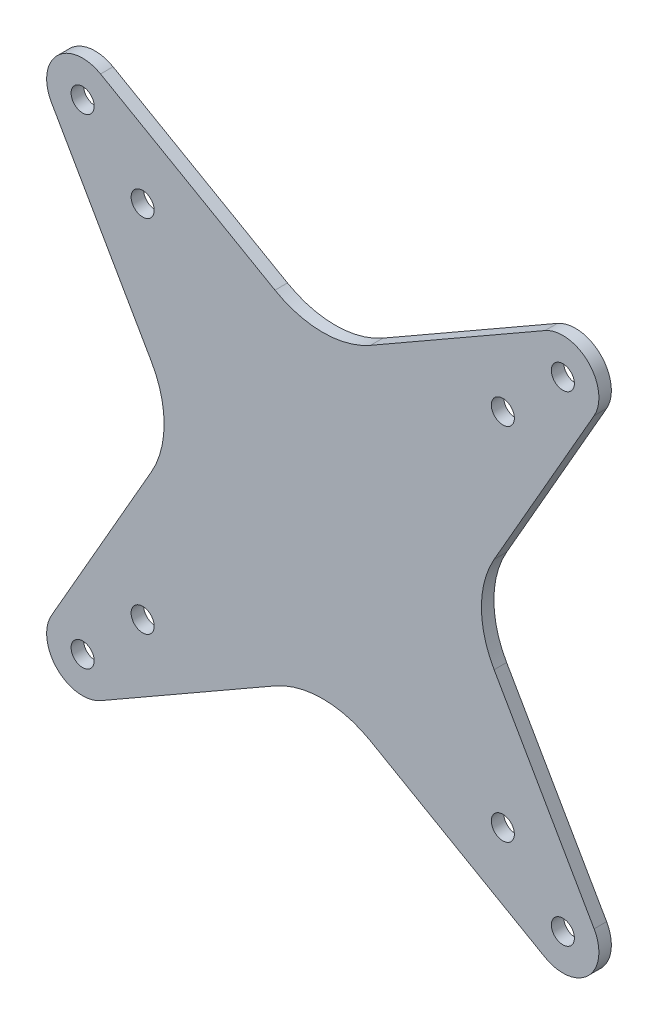
SolidWorks part; units mm, degrees
ref_plane "Front Plane" through (0, 0, 0) normal (0, 0, 1) x (1, 0, 0)
ref_plane "Top Plane" through (0, 0, 0) normal (0, 1, 0) x (1, 0, 0)
ref_plane "Right Plane" through (0, 0, 0) normal (1, 0, 0) x (0, 0, -1)
sketch "Sketch1" plane through (0, 0, 0) normal (0, 0, 1) x (1, 0, 0)
  line L0 (-53.033, 0) -> (0, -53.033) construction
  line L1 (-37.5, -37.5) -> (37.5, -37.5) construction
  line L2 (-37.5, -37.5) -> (-37.5, 37.5) construction
  line L3 (-37.5, 37.5) -> (37.5, 37.5) construction
  line L4 (37.5, -37.5) -> (37.5, 37.5) construction
  line L5 (-37.5, -37.5) -> (37.5, 37.5) construction
  line L6 (-37.5, 37.5) -> (37.5, -37.5) construction
  line L7 (-50, -50) -> (50, -50) construction
  line L8 (-50, -50) -> (-50, 50) construction
  line L9 (-50, 50) -> (50, 50) construction
  line L10 (50, -50) -> (50, 50) construction
  line L11 (-50, -50) -> (50, 50) construction
  line L12 (-50, 50) -> (50, -50) construction
  line L13 (-53.033, 0) -> (0, 53.033) construction
  line L14 (0, -53.033) -> (53.033, 0) construction
  line L15 (0, 53.033) -> (53.033, 0) construction
  line L16 (-53.033, 0) -> (53.033, 0) construction
  line L17 (0, -53.033) -> (0, 53.033) construction
  line L18 (-35.6823, 9.9475) -> (-56.5065, 46.2697)
  line L19 (-46.2697, 56.5065) -> (-9.9475, 35.6823)
  line L20 (9.9475, 35.6823) -> (46.2697, 56.5065)
  line L21 (56.5065, 46.2697) -> (35.6823, 9.9475)
  line L22 (35.6823, -9.9475) -> (56.5065, -46.2697)
  line L23 (46.2697, -56.5065) -> (9.9475, -35.6823)
  line L24 (-9.9475, -35.6823) -> (-46.2697, -56.5065)
  line L25 (-56.5065, -46.2697) -> (-35.6823, -9.9475)
  arc A0 (-46.2697, 56.5065) -> (-56.5065, 46.2697) centre (-50, 50) ccw
  arc A3 (-50, 42.5) -> (-42.5, 50) centre (-50, 50) ccw
  arc A4 (-56.5065, -46.2697) -> (-46.2697, -56.5065) centre (-50, -50) ccw
  arc A5 (35.6823, 9.9475) -> (35.6823, -9.9475) centre (53.033, 0) ccw
  arc A8 (-35.6823, -9.9475) -> (-35.6823, 9.9475) centre (-53.033, 0) ccw
  arc A9 (-9.9475, 35.6823) -> (9.9475, 35.6823) centre (0, 53.033) ccw
  arc A10 (56.5065, 46.2697) -> (46.2697, 56.5065) centre (50, 50) ccw
  arc A12 (46.2697, -56.5065) -> (56.5065, -46.2697) centre (50, -50) ccw
  arc A13 (9.9475, -35.6823) -> (-9.9475, -35.6823) centre (0, -53.033) ccw
  point P0 (0, 0)
  point P5 (0, 0)
  point P16 (0, 0)
  dimension "D5" = 75
  dimension "D6" = 20
  dimension "D7" = 15
  dimension "D1" = 100
  dimension "D2" = 100
  dimension "D3" = 75
  dimension "D4" = 75
extrude "Boss-Extrude1" add sketch "Sketch1" along normal blind 2.6
hole_wizard "M4 Clearance Hole1" positions "Sketch3" profile "Sketch2" hole size "M4" standard "DIN" end condition through all
sketch "Sketch3" plane through (0, 0, 0) normal (0, 0, 1) x (1, 0, 0)
  point P0 (-50, 50)
  point P3 (-37.5, 37.5)
  point P6 (37.5, 37.5)
  point P9 (50, 50)
  point P12 (50, -50)
  point P15 (37.5, -37.5)
  point P18 (-37.5, -37.5)
  point P21 (-50, -50)
sketch "Sketch2" plane through (-50, 50, 0) normal (1, 0, 0) x (0, 1, 0)
  line L0 (0, 0) -> (0, 2.6)
  line L1 (0, 2.6) -> (2.4, 2.6)
  line L2 (2.4, 2.6) -> (2.4, 0)
  line L5 (2.4, 0) -> (0, 0)
  line L11 (0, -6.35) -> (0, 107.95) construction
  dimension "Thru Hole Dia." = 4.8
  dimension "Thru Hole Depth" = 2.6
